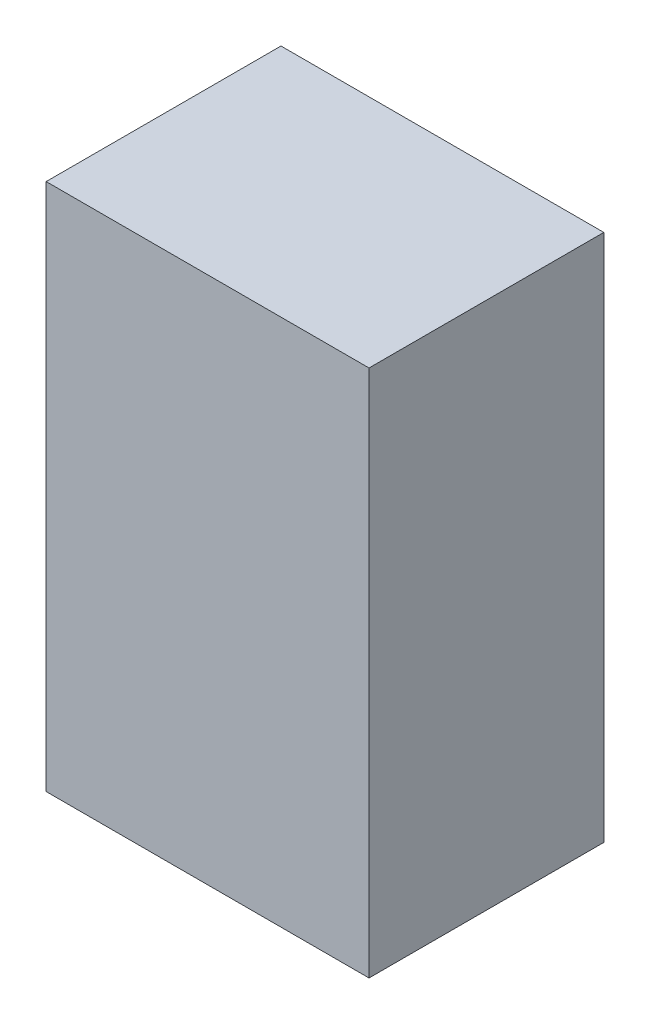
SolidWorks part; units mm, degrees
ref_plane "Front Plane" through (0, 0, 0) normal (0, 0, 1) x (1, 0, 0)
ref_plane "Top Plane" through (0, 0, 0) normal (0, 1, 0) x (1, 0, 0)
ref_plane "Right Plane" through (0, 0, 0) normal (1, 0, 0) x (0, 0, -1)
sketch "Sketch1" plane through (0, 0, 0) normal (0, 0, 1) x (1, 0, 0)
  line L1 (-49.53, 30.9562) -> (-3.81, 30.9562)
  line L2 (-49.53, 30.9562) -> (-49.53, -50.3238)
  line L3 (-49.53, -50.3238) -> (-3.81, -50.3238)
  line L4 (-3.81, 30.9562) -> (-3.81, -50.3238)
  dimension "D1" = 81.28
  dimension "D2" = 45.72
extrude "Boss-Extrude1" add sketch "Sketch1" along normal blind 7.62
ref_plane "Plane3" through (-3.81, -50.3238, 7.62) normal (0, 1, 0) x (1, 0, 0)
ref_plane "Plane4" through (-49.53, 30.9562, 0) normal (0, -1, 0) x (-1, 0, 0)
sketch "Sketch7" plane through (-49.53, 0, 0) normal (-1, 0, 0) x (0, 0, 1)
  line L0 (7.62, 30.9562) -> (7.62, -50.3238) construction
  line L1 (7.62, 30.9562) -> (-33.02, 30.9562)
  line L2 (7.62, 30.9562) -> (7.62, -50.3238)
  line L3 (7.62, -50.3238) -> (-33.02, -50.3238)
  line L4 (-33.02, 30.9562) -> (-33.02, -50.3238)
  dimension "D1" = 40.64
  dimension "D2" = 81.28
extrude "Boss-Extrude3" add sketch "Sketch7" along normal blind 5.08
sketch "Sketch8" plane through (-3.81, 0, 0) normal (1, 0, 0) x (0, 0, -1)
  line L1 (-7.62, 30.9562) -> (33.02, 30.9562)
  line L2 (-7.62, 30.9562) -> (-7.62, -50.3238)
  line L3 (-7.62, -50.3238) -> (33.02, -50.3238)
  line L4 (33.02, 30.9562) -> (33.02, -50.3238)
  dimension "D1" = 40.64
  dimension "D2" = 81.28
extrude "Boss-Extrude4" add sketch "Sketch8" along normal blind 5.08
sketch "Sketch9" plane through (0, 30.9562, 0) normal (0, 1, 0) x (1, 0, 0)
  line L1 (-54.61, -7.62) -> (1.27, -7.62)
  line L2 (-54.61, -7.62) -> (-54.61, 33.02)
  line L3 (-54.61, 33.02) -> (1.27, 33.02)
  line L4 (1.27, -7.62) -> (1.27, 33.02)
extrude "Boss-Extrude5" add sketch "Sketch9" along normal blind 5.08
sketch "Sketch10" plane through (0, -50.3238, 0) normal (0, -1, 0) x (1, 0, 0)
  line L1 (1.27, 7.62) -> (-54.61, 7.62)
  line L2 (1.27, 7.62) -> (1.27, -33.02)
  line L3 (1.27, -33.02) -> (-54.61, -33.02)
  line L4 (-54.61, 7.62) -> (-54.61, -33.02)
extrude "Boss-Extrude6" add sketch "Sketch10" along normal blind 5.08
